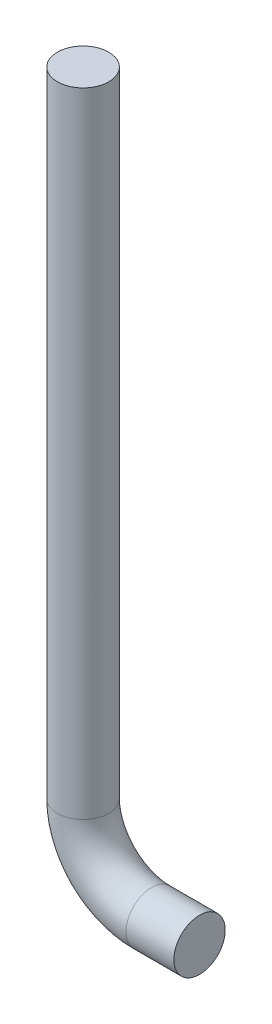
SolidWorks part; units mm, degrees
ref_plane "前视基准面" through (0, 0, 0) normal (0, 0, 1) x (1, 0, 0)
ref_plane "上视基准面" through (0, 0, 0) normal (0, 1, 0) x (1, 0, 0)
ref_plane "右视基准面" through (0, 0, 0) normal (1, 0, 0) x (0, 0, -1)
sketch "草图1" plane through (0, 0, 0) normal (0, 0, 1) x (1, 0, 0)
  line L0 (0, 0) -> (0, -185)
  line L1 (20, -205) -> (34, -205)
  arc A4 (20, -205) -> (0, -185) centre (20, -185) cw
  point P1 (165.3795, -228.33)
  point P2 (0, 0)
  point P3 (16.833, -228.4744)
  point P4 (14.4113, -228.4744)
  point P7 (40, -225.8996)
  point P8 (0, 0)
  dimension "D2" = 185
  dimension "D3" = 34
  dimension "D11" = 20
sketch "草图2" plane through (0, 0, 0) normal (0, 1, 0) x (1, 0, 0)
  circle A0 centre (0, 0) radius 7.5
  dimension "D1" = 15
sweep "扫描1" add profiles "草图2" path "草图1"
